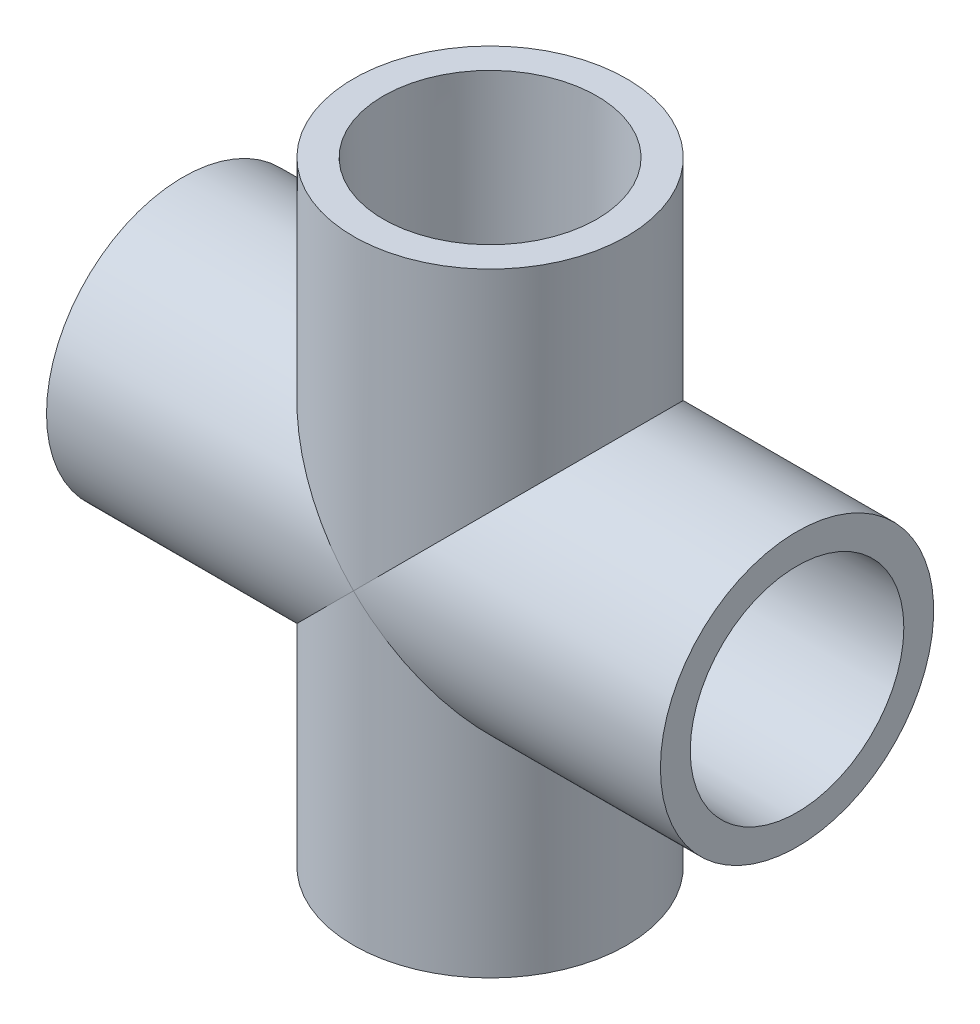
SolidWorks part; units mm, degrees
ref_plane "Front Plane" through (0, 0, 0) normal (0, 0, 1) x (1, 0, 0)
ref_plane "Top Plane" through (0, 0, 0) normal (0, 1, 0) x (1, 0, 0)
ref_plane "Right Plane" through (0, 0, 0) normal (1, 0, 0) x (0, 0, -1)
sketch "Sketch0" plane through (0, 0, 0) normal (0, 0, 1) x (1, 0, 0)
  line L0 (-30.9562, 0) -> (0, 0) construction
  line L1 (0, 0) -> (0, 30.9562) construction
  line L2 (-13.4937, 0) -> (0, 0) construction
  line L3 (0, 0) -> (0, 13.4937) construction
  line L4 (-30.9562, 13.7795) -> (-30.9562, -13.7795) construction
  line L5 (-13.4937, 10.6172) -> (-30.9562, 10.7696) construction
  line L6 (-13.4937, 10.6172) -> (-13.4937, -10.6172) construction
  line L7 (-13.4937, -10.6172) -> (-30.9562, -10.7696) construction
  line L8 (-30.9562, 10.7696) -> (-30.9562, -10.7696) construction
  line L9 (-13.7795, 30.9562) -> (13.7795, 30.9563) construction
  line L10 (-10.7696, 30.9562) -> (10.7696, 30.9563) construction
  line L11 (10.7696, 30.9563) -> (10.6172, 13.4937) construction
  line L12 (10.6172, 13.4937) -> (-10.6172, 13.4937) construction
  line L13 (-10.6172, 13.4937) -> (-10.7696, 30.9562) construction
  line L14 (-13.4937, 7.8994) -> (-13.4937, -7.8994) construction
  line L15 (-30.9562, 0) -> (-13.4937, 0) construction
  line L16 (0, 30.9562) -> (0, 13.4937) construction
  line L17 (0, 0) -> (13.4937, 0) construction
  line L18 (-7.8994, 13.4937) -> (7.8994, 13.4937) construction
  line L19 (13.4937, 0) -> (30.9562, 0) construction
  line L20 (0, 0) -> (0, -13.4937) construction
  line L21 (0, -13.4937) -> (0, -30.9562) construction
  dimension "H" = 30.9562
  dimension "G" = 13.4937
  dimension "M" = 27.559
  dimension "OD A" = 21.5392
  dimension "OD B" = 21.2344
  dimension "ID" = 15.7988
sketch "Sketch1" plane through (0, 0, 0) normal (0, 0, 1) x (1, 0, 0)
  line L0 (-30.9562, 0) -> (0, 0) construction
  line L1 (-30.9562, 0) -> (0, 0) construction
  line L2 (0, 0) -> (0, -13.7795) construction
  line L3 (-30.9562, -13.7795) -> (-13.4937, -13.7795)
  line L4 (-30.9562, -13.7795) -> (-30.9562, -10.7696)
  line L5 (-30.9562, -10.7696) -> (-13.4937, -10.6172)
  line L6 (-13.4937, -13.7795) -> (-13.4937, -10.6172)
  line L7 (-13.4937, -13.7795) -> (0, -13.7795) construction
  line L8 (30.9562, -10.7696) -> (13.4937, -10.6172)
  line L9 (30.9562, -13.7795) -> (30.9562, -10.7696)
  line L10 (13.4937, -13.7795) -> (13.4937, -10.6172)
  line L11 (30.9562, -13.7795) -> (13.4937, -13.7795)
revolve "Revolve1" add sketch "Sketch1" angle 360 about L1
sketch "Sketch2" plane through (0, 0, 0) normal (0, 0, 1) x (1, 0, 0)
  line L0 (10.7696, 30.9563) -> (10.6172, 13.4937)
  line L1 (10.6172, 13.4937) -> (13.7795, 13.4937)
  line L2 (13.7795, 13.4937) -> (13.7795, 30.9563)
  line L3 (13.7795, 30.9563) -> (10.7696, 30.9563)
  line L4 (0, 0) -> (0, 30.9562) construction
  line L5 (0, 0) -> (0, 30.9562) construction
  line L6 (0, 0) -> (13.4937, 0) construction
  line L7 (13.7795, -30.9563) -> (10.7696, -30.9563)
  line L8 (13.7795, -13.4937) -> (13.7795, -30.9563)
  line L9 (10.6172, -13.4937) -> (13.7795, -13.4937)
  line L10 (10.7696, -30.9563) -> (10.6172, -13.4937)
revolve "Revolve2" add sketch "Sketch2" angle 360 about L5
sketch "Sketch3" plane through (-13.4937, 0, 0) normal (1, 0, 0) x (0, 0, -1)
  circle A0 centre (0, 0) radius 7.8994
  circle A1 centre (0, 0) radius 13.7795
sketch "Sketch4" plane through (-13.4937, 0, 0) normal (1, 0, 0) x (0, 0, -1)
  circle A0 centre (0, 0) radius 13.7795 construction
  circle A1 centre (0, 0) radius 13.7795
extrude "Boss-Extrude1" add sketch "Sketch4" along normal up to vertex
sketch "Sketch5" plane through (0, 13.4938, 0) normal (0, -1, 0) x (1, 0, 0)
  circle A0 centre (0, 0) radius 13.7795 construction
  circle A1 centre (0, 0) radius 13.7795
extrude "Boss-Extrude2" add sketch "Sketch5" along normal up to vertex (26.9875 mm away) up to point (0, -13.4937, 0)
sketch "Sketch6" plane through (0, 0, 0) normal (0, 0, 1) x (1, 0, 0)
  line L0 (-30.9562, -10.7696) -> (-13.4937, -10.6172)
  line L1 (-13.4937, -10.6172) -> (-13.4937, -7.8994)
  line L2 (-13.4937, -7.8994) -> (13.4937, -7.8994)
  line L3 (13.4937, -10.2436) -> (13.4937, 10.2436) construction
  line L4 (0, -7.8994) -> (0, 0) construction
  line L5 (13.4937, -10.6172) -> (13.4937, -7.8994)
  line L6 (30.9562, -10.7696) -> (30.9562, 10.7696) construction
  line L7 (30.9562, -13.7795) -> (30.9562, 13.7795) construction
  line L8 (30.9562, -10.7696) -> (30.9563, 0)
  line L9 (30.9563, 0) -> (-30.9562, 0)
  line L10 (-30.9562, 0) -> (-30.9562, -10.7696)
  line L11 (30.9562, -10.7696) -> (13.4937, -10.6172)
revolve "Cut-Revolve1" cut sketch "Sketch6" angle 360 about L9
sketch "Sketch7" plane through (0, 0, 0) normal (0, 0, 1) x (1, 0, 0)
  line L0 (10.7696, 30.9563) -> (10.6172, 13.4937)
  line L1 (10.6172, 13.4937) -> (7.8994, 13.4937)
  line L2 (7.8994, 13.4937) -> (7.8994, -13.4938)
  line L4 (7.8994, 0) -> (0, 0) construction
  line L5 (0, 30.9562) -> (0, -30.9562)
  line L6 (-13.7795, 30.9562) -> (13.7795, 30.9563) construction
  line L7 (0, 30.9562) -> (10.7696, 30.9563)
  line L8 (10.6172, -13.4938) -> (7.8994, -13.4938)
  line L9 (10.7696, -30.9563) -> (10.6172, -13.4938)
  line L10 (0, 0) -> (13.4937, 0) construction
  line L11 (0, -30.9562) -> (10.7696, -30.9563)
revolve "Cut-Revolve2" cut sketch "Sketch7" angle 360 about L5
